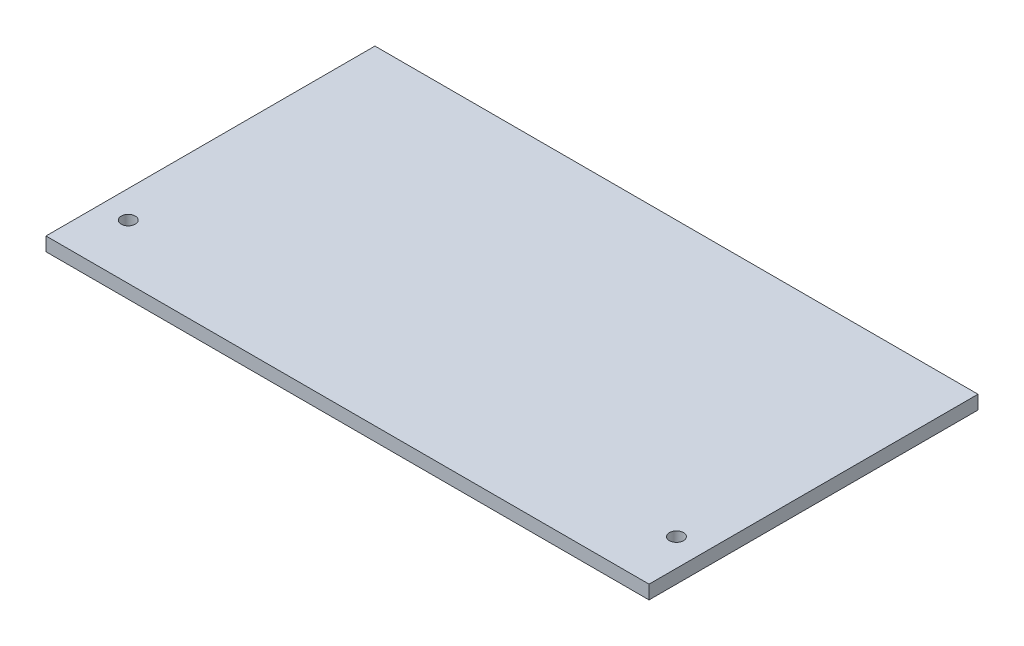
SolidWorks part; units mm, degrees
ref_plane "Front Plane" through (0, 0, 0) normal (0, 0, 1) x (1, 0, 0)
ref_plane "Top Plane" through (0, 0, 0) normal (0, 1, 0) x (1, 0, 0)
ref_plane "Right Plane" through (0, 0, 0) normal (1, 0, 0) x (0, 0, -1)
sketch "Sketch1" plane through (0, 0, 0) normal (0, 1, 0) x (1, 0, 0)
  line L0 (0, 76.2) -> (0, -76.2) construction
  line L1 (-139.7, 76.2) -> (139.7, 76.2)
  line L2 (-139.7, 76.2) -> (-139.7, -76.2)
  line L3 (-139.7, -76.2) -> (139.7, -76.2)
  line L4 (139.7, 76.2) -> (139.7, -76.2)
  line L5 (-139.7, 76.2) -> (139.7, -76.2) construction
  line L6 (-139.7, -76.2) -> (139.7, 76.2) construction
  line L7 (-127, -50.8) -> (0, -50.8) construction
  line L8 (0, -50.8) -> (127, -50.8) construction
  point P4 (0, 0)
  point P7 (-127, -50.8)
  point P8 (127, -50.8)
  point P10 (0, 0)
  dimension "D1" = 152.4
  dimension "D2" = 254
  dimension "D3" = 279.4
  dimension "D4" = 25.4
extrude "Boss-Extrude1" add sketch "Sketch1" along normal blind 6.35
sketch "Sketch4" plane through (0, 6.35, 0) normal (0, 1, 0) x (1, 0, 0)
  point P0 (-127, -50.8)
  point P3 (127, -50.8)
hole_wizard "F (0.257) Diameter Hole1" positions "Sketch4" profile "Sketch3" hole size "F" standard "ANSI Inch" end condition through all
sketch "Sketch3" plane through (-127, 6.35, 50.8) normal (1, 0, 0) x (0, 0, 1)
  line L0 (0, 0) -> (0, 6.35)
  line L1 (0, 6.35) -> (3.2639, 6.35)
  line L2 (3.2639, 6.35) -> (3.2639, 0)
  line L5 (3.2639, 0) -> (0, 0)
  line L11 (0, -6.35) -> (0, 107.95) construction
  dimension "Thru Hole Dia." = 6.5278
  dimension "Thru Hole Depth" = 6.35
